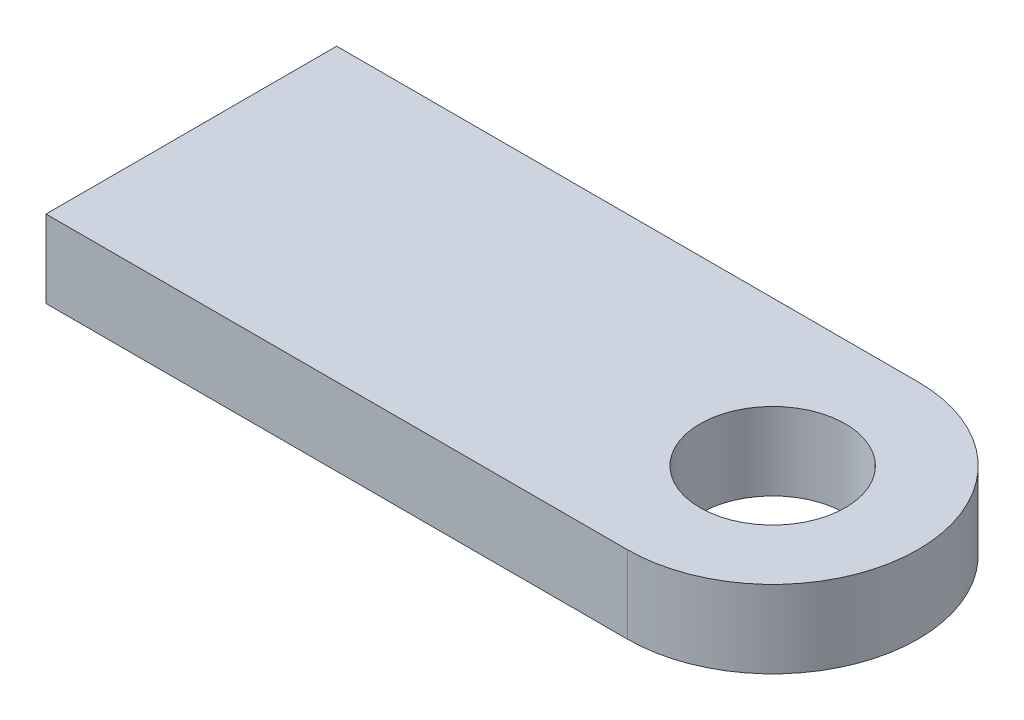
SolidWorks part; units mm, degrees
ref_plane "Front Plane" through (0, 0, 0) normal (0, 0, 1) x (1, 0, 0)
ref_plane "Top Plane" through (0, 0, 0) normal (0, 1, 0) x (1, 0, 0)
ref_plane "Right Plane" through (0, 0, 0) normal (1, 0, 0) x (0, 0, -1)
sketch "Sketch1" plane through (0, 0, 0) normal (0, 1, 0) x (1, 0, 0)
  line L0 (0, 0) -> (15.24, 0)
  line L1 (15.24, -7.62) -> (0, -7.62)
  line L2 (0, -7.62) -> (0, 0)
  arc A0 (15.24, 0) -> (15.24, -7.62) centre (15.24, -3.81) cw
  dimension "D1" = 7.62
  dimension "D2" = 15.24
  dimension "D3" = 7.62
extrude "Boss-Extrude1" add sketch "Sketch1" along normal blind 2.032
sketch "Sketch2" plane through (0, 2.032, 0) normal (0, 1, 0) x (1, 0, 0)
  line L0 (15.24, 0) -> (15.24, -7.62) construction
  arc A0 (15.24, -7.62) -> (15.24, 0) centre (15.24, -3.81) ccw construction
  circle A1 centre (15.24, -3.81) radius 1.905
  dimension "D1" = 3.81
extrude "Cut-Extrude1" cut sketch "Sketch2" against normal through all
